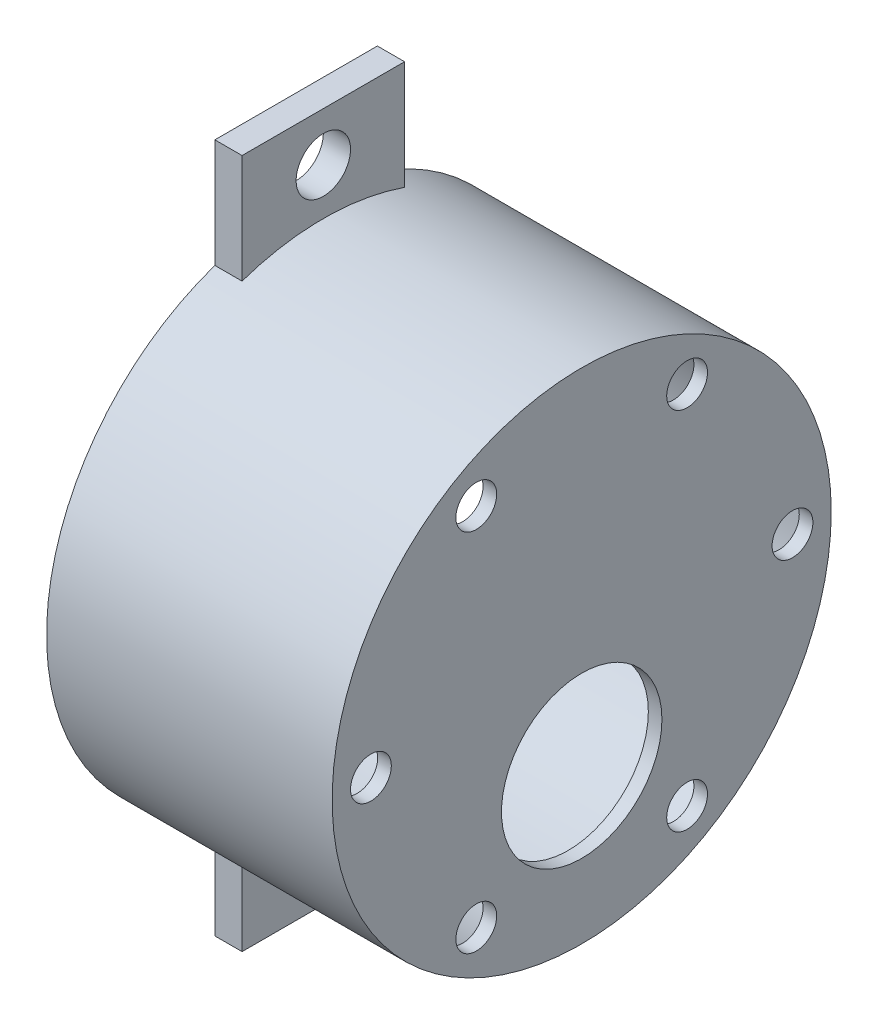
SolidWorks part; units mm, degrees
ref_plane "Front Plane" through (0, 0, 0) normal (0, 0, 1) x (1, 0, 0)
ref_plane "Top Plane" through (0, 0, 0) normal (0, 1, 0) x (1, 0, 0)
ref_plane "Right Plane" through (0, 0, 0) normal (1, 0, 0) x (0, 0, -1)
sketch "Sketch1" plane through (0, 0, 0) normal (1, 0, 0) x (0, 0, -1)
  circle A1 centre (0, 0) radius 18.35
  dimension "D1" = 36.7
extrude "Boss-Extrude1" add sketch "Sketch1" against normal blind 21
shell "Shell1" thickness 1
sketch "Sketch3" plane through (0, 0, 0) normal (1, 0, 0) x (0, 0, -1)
  line L1 (15.5, 0) -> (7.75, 13.4234)
  line L2 (7.75, 13.4234) -> (-7.75, 13.4234)
  line L3 (-7.75, 13.4234) -> (-15.5, 0)
  line L4 (-15.5, 0) -> (-7.75, -13.4234)
  line L5 (-7.75, -13.4234) -> (7.75, -13.4234)
  line L6 (7.75, -13.4234) -> (15.5, 0)
  circle A0 centre (0, 0) radius 13.4234 construction
  circle A1 centre (-7.75, 13.4234) radius 1.5
  point P12 (0, 13.4234)
  dimension "D2" = 3
  dimension "D1" = 15.5
extrude "Cut-Extrude2" cut sketch "Sketch3" against normal up to surface (1 mm away) contours A1 up to face at (-1, 0, -17.35)
pattern_circular "CirPattern1" count 6 over 360 about axis through (0, 0, 0) along (1, 0, 0) of "Cut-Extrude2"
sketch "Sketch4" plane through (0, 0, 0) normal (1, 0, 0) x (0, 0, -1)
  circle A0 centre (0, -7) radius 5.9
  circle A1 centre (-15.5, 0) radius 1.5 construction
  dimension "D1" = 11.8
  dimension "D2" = 7
extrude "Cut-Extrude3" cut sketch "Sketch4" against normal blind 10
sketch "Sketch5" plane through (-21, 0, 0) normal (-1, 0, 0) x (0, 0, 1)
  line L1 (-5.9749, 17.35) -> (5.9749, 17.35)
  line L2 (-5.9749, 17.35) -> (-5.9749, 25.35)
  line L3 (-5.9749, 25.35) -> (5.9749, 25.35)
  line L4 (5.9749, 17.35) -> (5.9749, 25.35)
  circle A1 centre (0, 0) radius 17.35 construction
  circle A3 centre (0, 0) radius 18.35 construction
  point P6 (-5.9247, 17.3144)
  point P9 (5.8167, 17.3)
  point P10 (5.9712, 17.2984)
  dimension "D1" = 8
extrude "Boss-Extrude2" add sketch "Sketch5" against normal blind 2
sketch "Sketch6" plane through (-19, 0, 0) normal (1, 0, 0) x (0, 0, -1)
  circle A0 centre (0, 21.7639) radius 2
  dimension "D1" = 4
extrude "Cut-Extrude4" cut sketch "Sketch6" against normal blind 2
mirror "Mirror1" about plane through (0, 0, 0) normal (0, 1, 0) of "Cut-Extrude4", "Boss-Extrude2"
